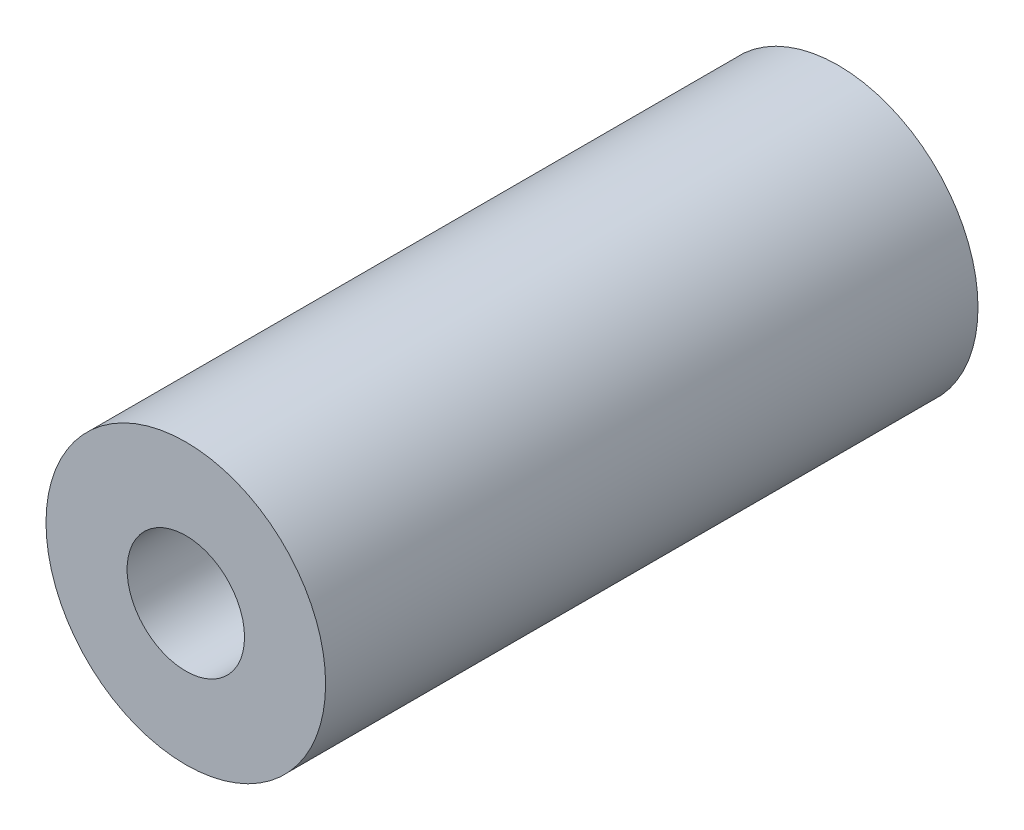
SolidWorks part; units mm, degrees
material "PE Low/Medium Density"
ref_plane "Front Plane" through (0, 0, 0) normal (0, 0, 1) x (1, 0, 0)
ref_plane "Top Plane" through (0, 0, 0) normal (0, 1, 0) x (1, 0, 0)
ref_plane "Right Plane" through (0, 0, 0) normal (1, 0, 0) x (0, 0, -1)
sketch "Sketch1" plane through (0, 0, 0) normal (0, 0, 1) x (1, 0, 0)
  circle A0 centre (0, 0) radius 9.525
  circle A1 centre (0, 0) radius 4.0005
  dimension "OD" = 19.05
  dimension "ID" = 8.001
extrude "Extrude1" add sketch "Sketch1" along normal mid plane 44.45
sketch "Sketch2" plane through (0, 0, 0) normal (1, 0, 0) x (0, 0, -1)
  line L0 (-22.225, -4.0005) -> (22.225, -4.0005) construction
  line L3 (22.225, 4.0005) -> (-22.225, 4.0005) construction
  line L5 (-22.225, -4.0005) -> (22.225, -4.0005)
  line L6 (22.225, 4.0005) -> (-22.225, 4.0005)
sketch "Sketch4" plane through (0, 0, 22.225) normal (0, 0, 1) x (1, 0, 0)
  line L0 (0, 0) -> (-2.8288, 2.8288)
  line L1 (0, -5.2388) -> (0, 5.2388) construction
  circle A0 centre (0, 0) radius 4.0005 construction
  dimension "D1" = 45
